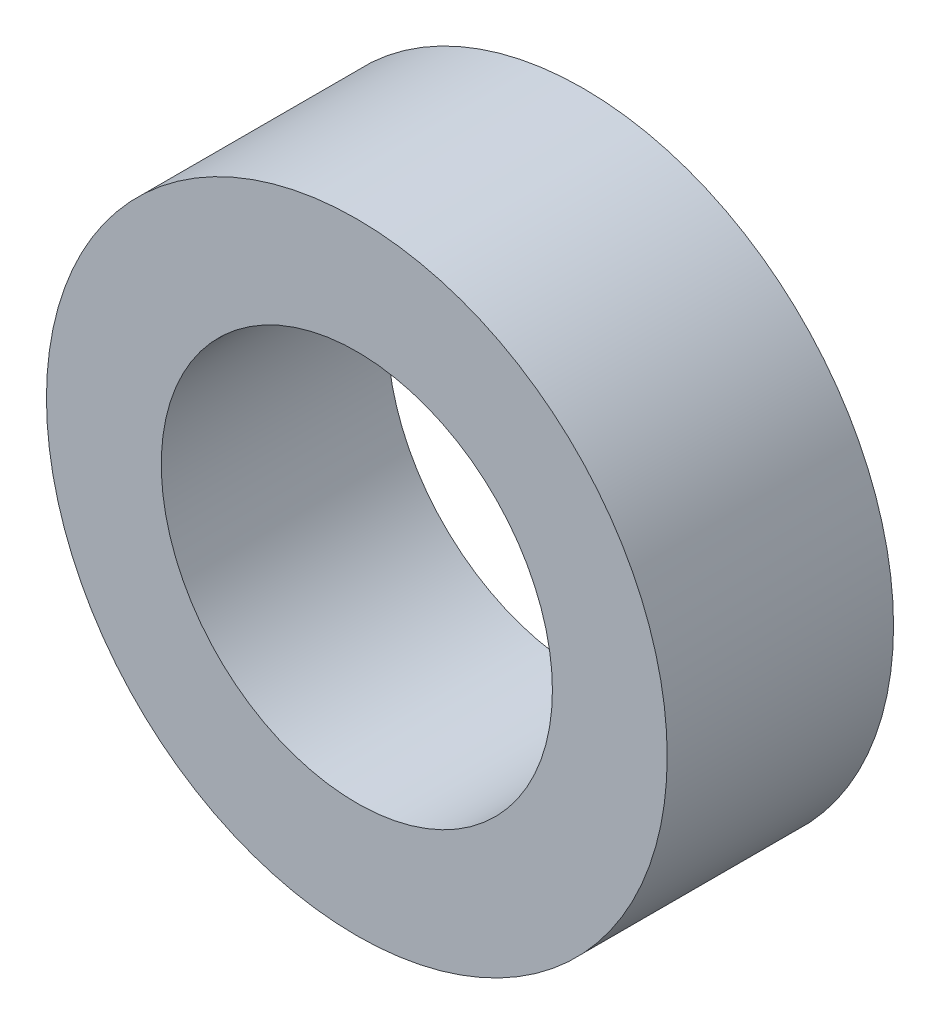
SolidWorks part; units mm, degrees
ref_plane "Piano frontale" through (0, 0, 0) normal (0, 0, 1) x (1, 0, 0)
ref_plane "Piano superiore" through (0, 0, 0) normal (0, 1, 0) x (1, 0, 0)
ref_plane "Piano destro" through (0, 0, 0) normal (1, 0, 0) x (0, 0, -1)
sketch "Schizzo1" plane through (0, 0, 0) normal (0, 0, 1) x (1, 0, 0)
  circle A0 centre (0, 0) radius 2.99
  circle A1 centre (0, 0) radius 4.745
  dimension "D1" = 5.98
  dimension "D2" = 9.49
extrude "Estrusione-Estrusione1" add sketch "Schizzo1" along normal blind 3.46
